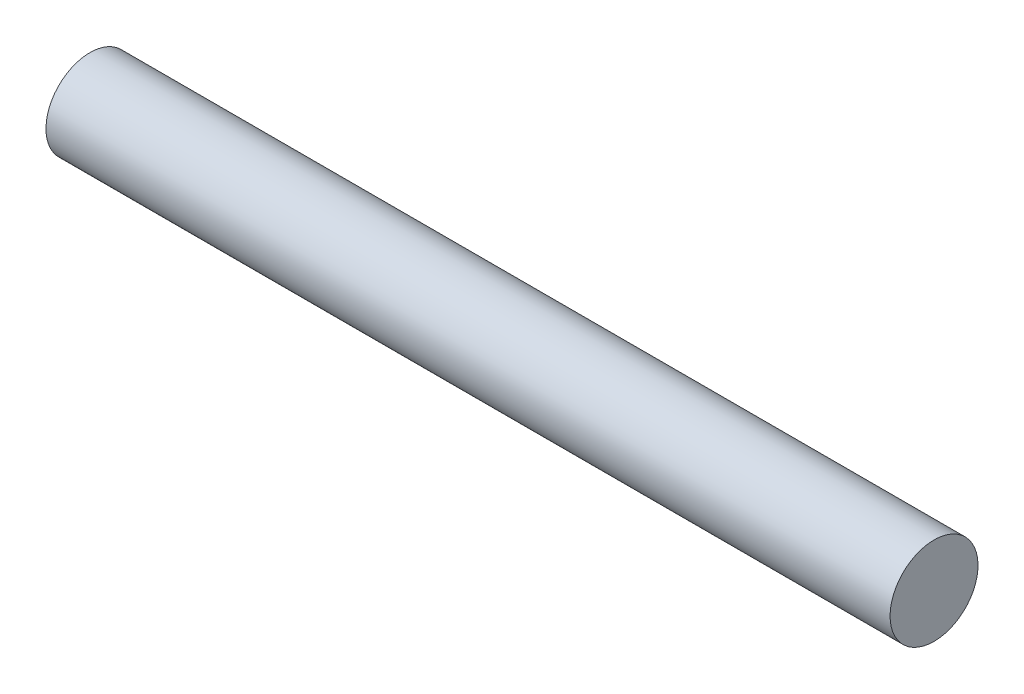
SolidWorks part; units mm, degrees
ref_plane "Ön Düzlem" through (0, 0, 0) normal (0, 0, 1) x (1, 0, 0)
ref_plane "Üst Düzlem" through (0, 0, 0) normal (0, 1, 0) x (1, 0, 0)
ref_plane "Sağ Düzlem" through (0, 0, 0) normal (1, 0, 0) x (0, 0, -1)
sketch "Sketch2" plane through (0, 0, 0) normal (0, 0, 1) x (1, 0, 0)
  line L1 (-85.8469, 3.1888) -> (10.1531, 3.1888)
  line L2 (-85.8469, 3.1888) -> (-85.8469, -1.8112)
  line L3 (-85.8469, -1.8112) -> (10.1531, -1.8112)
  line L4 (10.1531, 3.1888) -> (10.1531, -1.8112)
  dimension "D1" = 5
  dimension "D2" = 96
revolve "Revolve1" add sketch "Sketch2" angle 360 about L1
